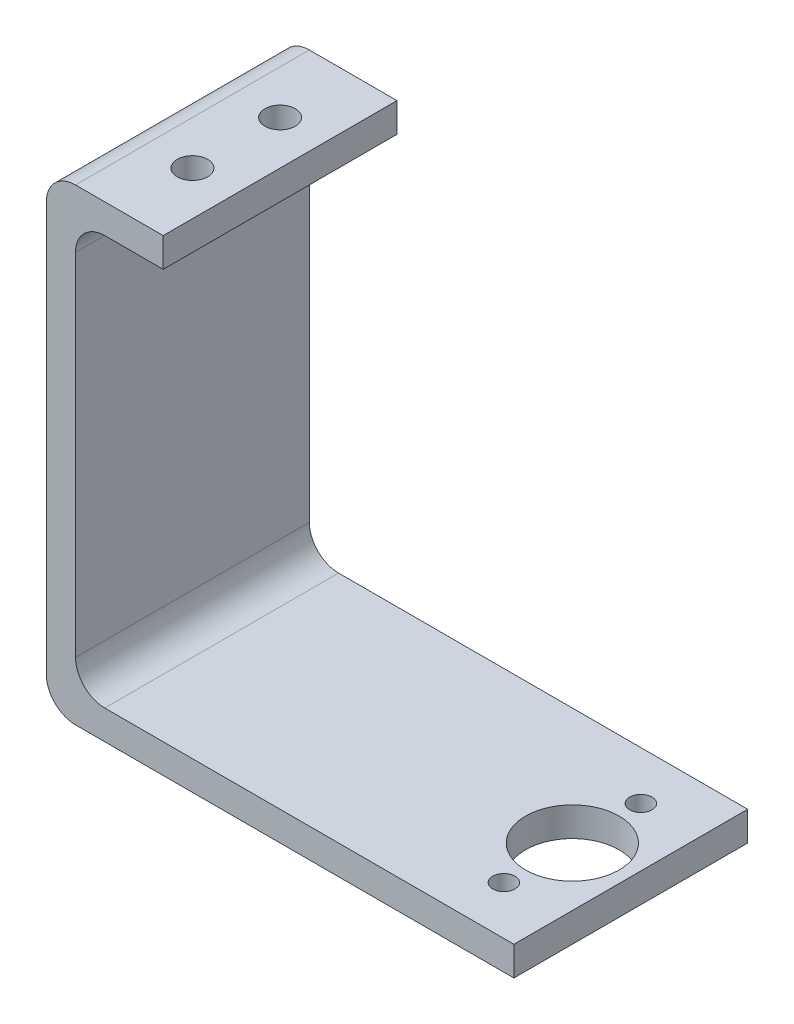
SolidWorks part; units mm, degrees
ref_plane "Front Plane" through (0, 0, 0) normal (0, 0, 1) x (1, 0, 0)
ref_plane "Top Plane" through (0, 0, 0) normal (0, 1, 0) x (1, 0, 0)
ref_plane "Right Plane" through (0, 0, 0) normal (1, 0, 0) x (0, 0, -1)
sketch "Sketch1" plane through (0, 0, 0) normal (0, 0, 1) x (1, 0, 0)
  line L0 (-17.0593, 26.9872) -> (-29.7593, 26.9872)
  line L1 (-29.7593, 26.9872) -> (-29.7593, -23.8128)
  line L2 (-29.7593, -23.8128) -> (21.0407, -23.8128)
  line L3 (-17.0593, 23.8122) -> (-26.5843, 23.8122)
  line L4 (-26.5843, 23.8122) -> (-26.5843, -20.6378)
  line L5 (-26.5843, -20.6378) -> (21.0407, -20.6378)
  line L6 (-17.0593, 26.9872) -> (-17.0593, 23.8122)
  line L7 (21.0407, -23.8128) -> (21.0407, -20.6378)
  dimension "D2" = 12.7
  dimension "D3" = 50.8
  dimension "D4" = 50.8
  dimension "D1" = 3.175
extrude "Boss-Extrude1" add sketch "Sketch1" along normal blind 25.4
hole_wizard "M4x0.7 Tapped Hole1" positions "Sketch6" profile "Sketch5" tap size "M4x0.7" standard "ANSI Metric"
sketch "Sketch6" plane through (0, 26.9872, 0) normal (0, 1, 0) x (1, 0, 0)
  line L1 (-17.0593, -25.4) -> (-17.0593, 0) construction
  line L2 (-17.0593, 0) -> (-29.7593, 0) construction
  point P0 (-21.8218, -7.9375)
  point P2 (-21.8218, -17.4625)
  dimension "D1" = 4.7625
  dimension "D2" = 9.525
  dimension "D3" = 7.9375
sketch "Sketch5" plane through (-21.8218, 26.9872, 7.9375) normal (1, 0, 0) x (0, 0, 1)
  line L0 (0, 0) -> (0, 10.8974)
  line L1 (0, 10.8974) -> (1.65, 9.906)
  line L2 (1.65, 9.906) -> (1.65, 0)
  line L5 (1.65, 0) -> (0, 0)
  line L10 (0, 10.8974) -> (-1.65, 9.906) construction
  line L11 (0, -6.35) -> (0, 107.95) construction
  dimension "Tap Drill Dia." = 3.3
  dimension "Tap Drill Depth" = 9.906
  dimension "Drill Angle" = 118
sketch "Sketch7" plane through (0, -23.8128, 0) normal (0, -1, 0) x (1, 0, 0)
  line L0 (-29.7593, 25.4) -> (21.0407, 25.4) construction
  line L1 (21.0407, 25.4) -> (21.0407, 0) construction
  circle A0 centre (14.6907, 12.7) radius 5.08
  circle A1 centre (14.6907, 12.7) radius 7.4422 construction
  circle A2 centre (14.6907, 5.2578) radius 1.2065
  circle A3 centre (14.6907, 20.1422) radius 1.2065
  dimension "D3" = 10.16
  dimension "D4" = 14.8844
  dimension "D5" = 2.413
  dimension "D1" = 12.7
  dimension "D2" = 6.35
extrude "Cut-Extrude1" cut sketch "Sketch7" against normal up to next
fillet "Fillet1" radius 3.175 2 edges at (-29.7593, -23.8128, 12.7) (-29.7593, 26.9872, 12.7)
fillet "Fillet2" radius 3.175 2 edges at (-26.5843, 23.8122, 12.7) (-26.5843, -20.6378, 12.7)
